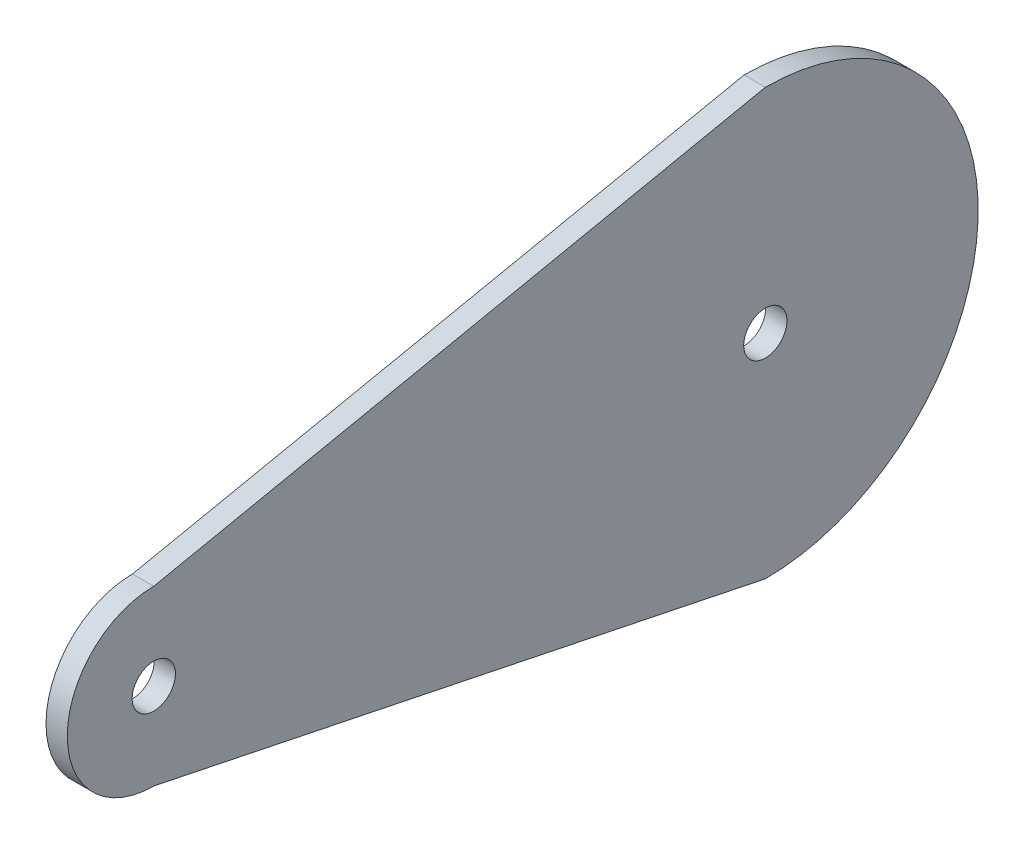
SolidWorks part; units mm, degrees
material "ABS"
ref_plane "Front Plane" through (0, 0, 0) normal (0, 0, 1) x (1, 0, 0)
ref_plane "Top Plane" through (0, 0, 0) normal (0, 1, 0) x (1, 0, 0)
ref_plane "Right Plane" through (0, 0, 0) normal (1, 0, 0) x (0, 0, -1)
sketch "Sketch1" plane through (0, 0, 0) normal (1, 0, 0) x (0, 0, -1)
  line L0 (0, 0) -> (72.9742, 0) construction
  line L1 (0, 10.3233) -> (72.9742, 25.4)
  line L2 (0, -10.3233) -> (72.9742, -25.4)
  circle A0 centre (0, 0) radius 2.5808
  circle A1 centre (0, 0) radius 10.3233
  circle A2 centre (72.9742, 0) radius 25.4
  circle A3 centre (72.9742, 0) radius 2.5808
  dimension "D1" = 72.9742
extrude "Boss-Extrude1" add sketch "Sketch1" along normal blind 2.54
